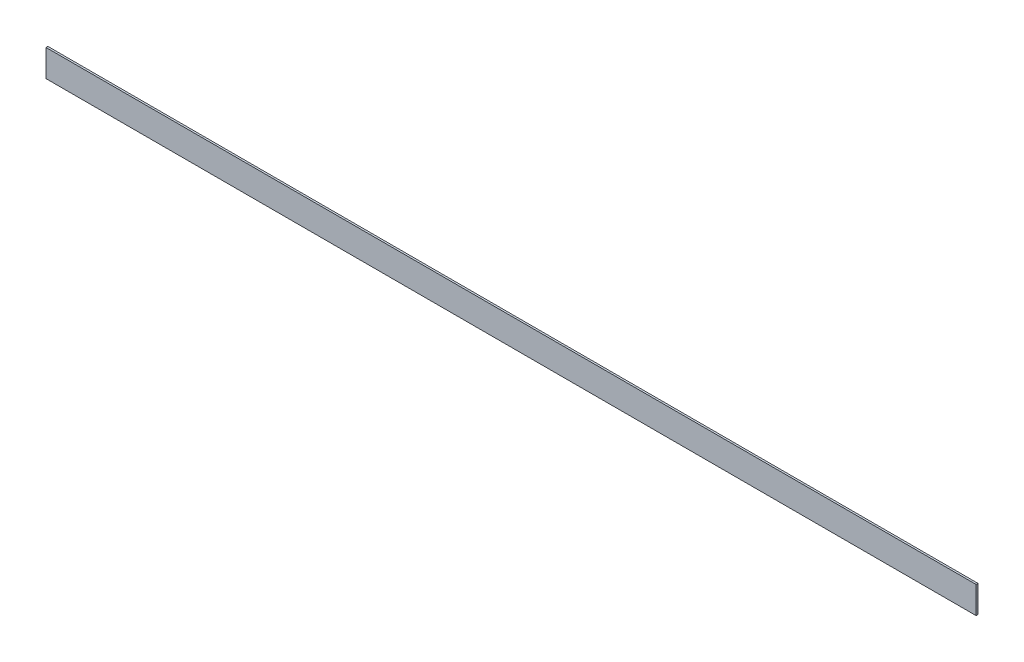
SolidWorks part; units mm, degrees
ref_plane "Front Plane" through (0, 0, 0) normal (0, 0, 1) x (1, 0, 0)
ref_plane "Top Plane" through (0, 0, 0) normal (0, 1, 0) x (1, 0, 0)
ref_plane "Right Plane" through (0, 0, 0) normal (1, 0, 0) x (0, 0, -1)
sketch "Sketch1" plane through (0, 0, 0) normal (0, 1, 0) x (1, 0, 0)
  line L1 (155, 0.315) -> (-155, 0.315)
  line L2 (155, 0.315) -> (155, -0.315)
  line L3 (155, -0.315) -> (-155, -0.315)
  line L4 (-155, 0.315) -> (-155, -0.315)
  line L5 (155, 0.315) -> (-155, -0.315) construction
  line L6 (155, -0.315) -> (-155, 0.315) construction
  point P0 (0, 0)
  dimension "D1" = 0.63
  dimension "D2" = 310
extrude "Boss-Extrude1" add sketch "Sketch1" along normal blind 9
